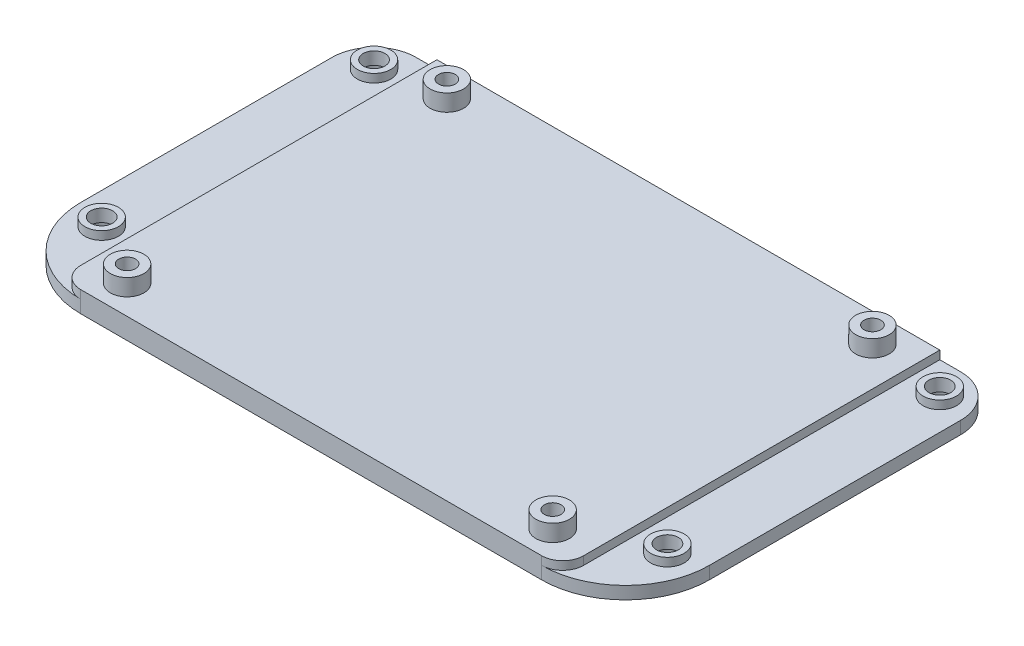
SolidWorks part; units mm, degrees
ref_plane "Front Plane" through (0, 0, 0) normal (0, 0, 1) x (1, 0, 0)
ref_plane "Top Plane" through (0, 0, 0) normal (0, 1, 0) x (1, 0, 0)
ref_plane "Right Plane" through (0, 0, 0) normal (1, 0, 0) x (0, 0, -1)
sketch "Sketch1" plane through (0, 0, 0) normal (0, 1, 0) x (1, 0, 0)
  line L1 (0, 0) -> (120, 0)
  line L2 (0, 0) -> (0, 90)
  line L3 (0, 90) -> (120, 90)
  line L4 (120, 0) -> (120, 90)
  dimension "D1" = 90
  dimension "D2" = 120
extrude "Boss-Extrude1" add sketch "Sketch1" along normal blind 2
sketch "Sketch2" plane through (0, 2, 0) normal (0, 1, 0) x (1, 0, 0)
  line L0 (120, 90) -> (0, 90) construction
  line L1 (9.225, 83.15) -> (110.775, 83.15) construction
  line L2 (9.225, 83.15) -> (9.225, 6.85) construction
  line L3 (9.225, 6.85) -> (110.775, 6.85) construction
  line L4 (110.775, 83.15) -> (110.775, 6.85) construction
  line L5 (120, 0) -> (120, 90) construction
  circle A0 centre (9.225, 83.15) radius 4
  circle A1 centre (9.225, 6.85) radius 4
  circle A2 centre (110.775, 83.15) radius 4
  circle A3 centre (110.775, 6.85) radius 4
  circle A4 centre (9.225, 83.15) radius 2
  circle A5 centre (110.775, 83.15) radius 2
  circle A6 centre (110.775, 6.85) radius 2
  circle A7 centre (9.225, 6.85) radius 2
  point P12 (60, 90)
  point P15 (60, 83.15)
  point P18 (120, 45)
  point P19 (110.775, 45)
  dimension "D1" = 8
  dimension "D2" = 8
  dimension "D3" = 8
  dimension "D4" = 8
  dimension "D5" = 4
  dimension "D6" = 4
  dimension "D7" = 4
  dimension "D8" = 4
  dimension "D9" = 101.55
  dimension "D10" = 76.3
extrude "Boss-Extrude2" add sketch "Sketch2" along normal blind 4
fillet "Fillet1" radius 5 2 edges at (0, 1, 0) (120, 1, 0)
sketch "Sketch3" plane through (0, 0, 0) normal (0, -1, 0) x (1, 0, 0)
  line L4 (0, -90) -> (0, -5) construction
  line L5 (5, 0) -> (115, 0)
  line L6 (-15, -20) -> (-15, -80)
  line L7 (-5, -90) -> (125, -90)
  line L8 (135, -20) -> (135, -80)
  line L9 (120, -5) -> (120, -90) construction
  line L10 (5, 0) -> (115, 0) construction
  line L11 (120, -90) -> (0, -90) construction
  arc A0 (115, 0) -> (135, -20) centre (115, -20) cw
  arc A1 (125, -90) -> (135, -80) centre (125, -80) ccw
  arc A2 (-15, -80) -> (-5, -90) centre (-5, -80) ccw
  arc A3 (5, 0) -> (-15, -20) centre (5, -20) ccw
  dimension "D5" = 20
  dimension "D6" = 20
  dimension "D7" = 10
  dimension "D8" = 10
  dimension "D1" = 15
  dimension "D2" = 15
  dimension "D3" = 0
  dimension "D4" = 0
extrude "Boss-Extrude3" add sketch "Sketch3" along normal blind 3
sketch "Sketch4" plane through (0, -3, 0) normal (0, -1, 0) x (1, 0, 0)
  line L1 (-7.5, -82.5) -> (127.5, -82.5) construction
  line L2 (-7.5, -82.5) -> (-7.5, -17.5) construction
  line L3 (-7.5, -17.5) -> (127.5, -17.5) construction
  line L4 (127.5, -82.5) -> (127.5, -17.5) construction
  line L5 (-7.5, -82.5) -> (127.5, -17.5) construction
  line L6 (-7.5, -17.5) -> (127.5, -82.5) construction
  line L7 (115, 0) -> (5, 0) construction
  circle A0 centre (-7.5, -17.5) radius 4.5
  circle A1 centre (-7.5, -82.5) radius 4.5
  circle A2 centre (127.5, -17.5) radius 4.5
  circle A3 centre (127.5, -82.5) radius 4.5
  point P0 (60, -50)
  point P7 (60, 0)
  dimension "D2" = 50
  dimension "D3" = 9
  dimension "D1" = 135
  dimension "72" = 65
extrude "Cut-Extrude1" cut sketch "Sketch4" against normal blind 2
sketch "Sketch5" plane through (0, 0, 0) normal (0, 1, 0) x (1, 0, 0)
  line L1 (-7.5, 17.5) -> (127.5, 17.5) construction
  line L2 (-7.5, 17.5) -> (-7.5, 82.5) construction
  line L3 (-7.5, 82.5) -> (127.5, 82.5) construction
  line L4 (127.5, 17.5) -> (127.5, 82.5) construction
  circle A0 centre (-7.5, 17.5) radius 2.6
  circle A1 centre (127.5, 17.5) radius 2.6
  circle A2 centre (-7.5, 82.5) radius 2.6
  circle A3 centre (127.5, 82.5) radius 2.6
  circle A4 centre (-7.5, 17.5) radius 4
  circle A5 centre (127.5, 17.5) radius 4
  circle A6 centre (127.5, 82.5) radius 4
  circle A7 centre (-7.5, 82.5) radius 4
  dimension "D1" = 135
  dimension "D5" = 5.2
  dimension "D6" = 8
  dimension "D2" = 65
  dimension "D3" = 17.5
  dimension "D4" = 7.5
extrude "Boss-Extrude4" add sketch "Sketch5" along normal blind 2
sketch "Sketch6" plane through (0, 0, 0) normal (0, 1, 0) x (1, 0, 0)
  circle A0 centre (-7.5, 17.5) radius 2.6 construction
  circle A1 centre (127.5, 17.5) radius 2.6 construction
  circle A2 centre (127.5, 82.5) radius 2.6 construction
  circle A3 centre (-7.5, 82.5) radius 2.6 construction
  circle A4 centre (-7.5, 17.5) radius 2.6
  circle A5 centre (127.5, 17.5) radius 2.6
  circle A6 centre (127.5, 82.5) radius 2.6
  circle A7 centre (-7.5, 82.5) radius 2.6
extrude "Cut-Extrude2" cut sketch "Sketch6" against normal through all
sketch "Sketch7" plane through (0, 6, 0) normal (0, 1, 0) x (1, 0, 0)
  circle A0 centre (110.775, 83.15) radius 2 construction
  circle A1 centre (110.775, 6.85) radius 2 construction
  circle A2 centre (9.225, 6.85) radius 2 construction
  circle A3 centre (9.225, 83.15) radius 2 construction
  circle A4 centre (110.775, 83.15) radius 2
  circle A5 centre (110.775, 6.85) radius 2
  circle A6 centre (9.225, 6.85) radius 2
  circle A7 centre (9.225, 83.15) radius 2
extrude "Cut-Extrude3" cut sketch "Sketch7" against normal blind 6.7
ref_plane "Plane1" through (60, 0, 0) normal (-1, 0, 0) x (0, 0, 1)
